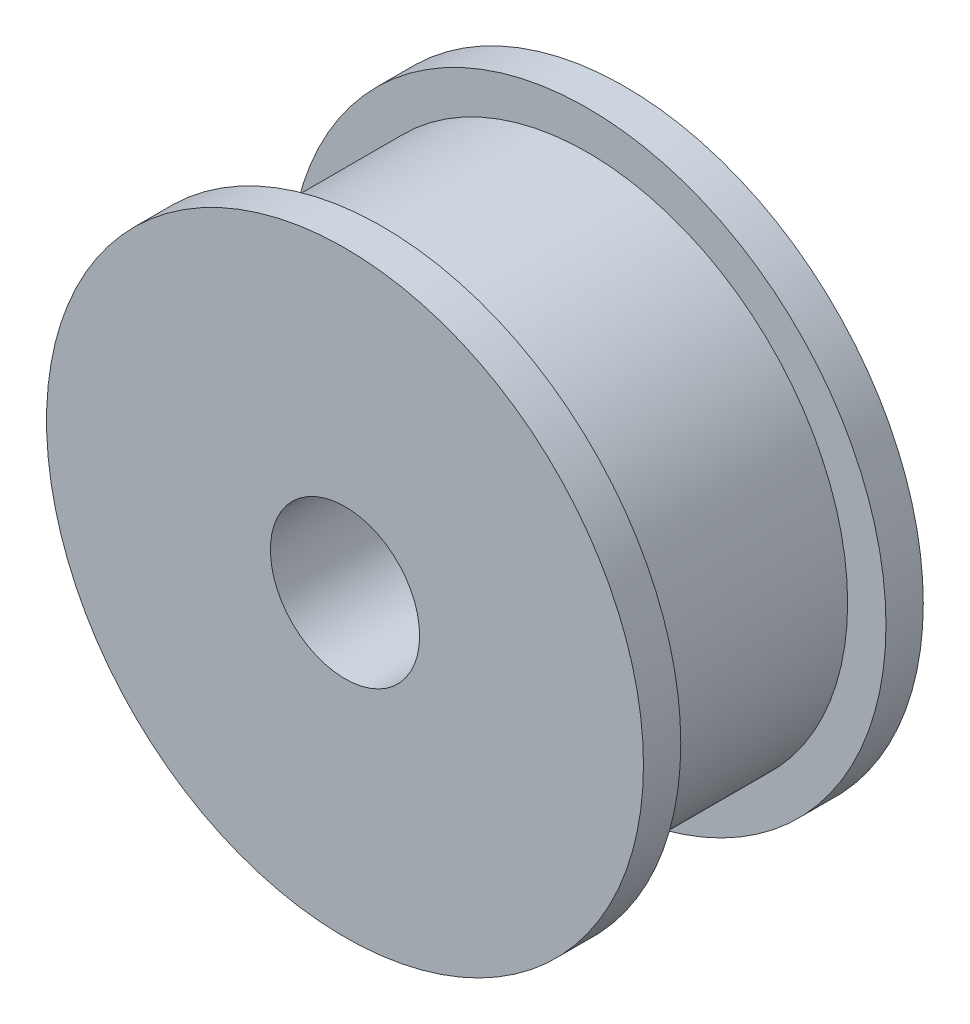
SolidWorks part; units mm, degrees
ref_plane "前视基准面" through (0, 0, 0) normal (0, 0, 1) x (1, 0, 0)
ref_plane "上视基准面" through (0, 0, 0) normal (0, 1, 0) x (1, 0, 0)
ref_plane "右视基准面" through (0, 0, 0) normal (1, 0, 0) x (0, 0, -1)
sketch "草图1" plane through (0, 0, 0) normal (0, 0, 1) x (1, 0, 0)
  circle A0 centre (0, 0) radius 16
  dimension "D1" = 32
extrude "凸台-拉伸1" add sketch "草图1" along normal blind 2 contours A0
sketch "草图2" plane through (0, 0, 2) normal (0, 0, 1) x (1, 0, 0)
  circle A0 centre (0, 0) radius 13.945
  dimension "D1" = 27.89
extrude "凸台-拉伸2" add sketch "草图2" along normal blind 11
sketch "草图3" plane through (0, 0, 13) normal (0, 0, 1) x (1, 0, 0)
  circle A0 centre (0, 0) radius 16
  dimension "D1" = 32
extrude "凸台-拉伸3" add sketch "草图3" along normal blind 2
sketch "草图4" plane through (0, 0, 15) normal (0, 0, 1) x (1, 0, 0)
  circle A0 centre (0, 0) radius 4
  dimension "D1" = 8
extrude "切除-拉伸1" cut sketch "草图4" against normal blind 15
sketch "草图5" plane through (0, 0, 0) normal (0, 1, 0) x (1, 0, 0)
  line L0 (0, 0) -> (0, -15) construction
  line L1 (-16, -15) -> (16, -15) construction
  circle A0 centre (0, -7.5) radius 2
extrude "切除-拉伸2" cut sketch "草图5" against normal blind 20
sketch "草图8" plane through (0, 0, 0) normal (1, 0, 0) x (0, 0, -1)
  line L0 (-15, 0) -> (0, 0) construction
  line L1 (-15, 16) -> (-15, -16) construction
  circle A0 centre (-7.5, 0) radius 2
extrude "切除-拉伸3" cut sketch "草图8" against normal blind 20
